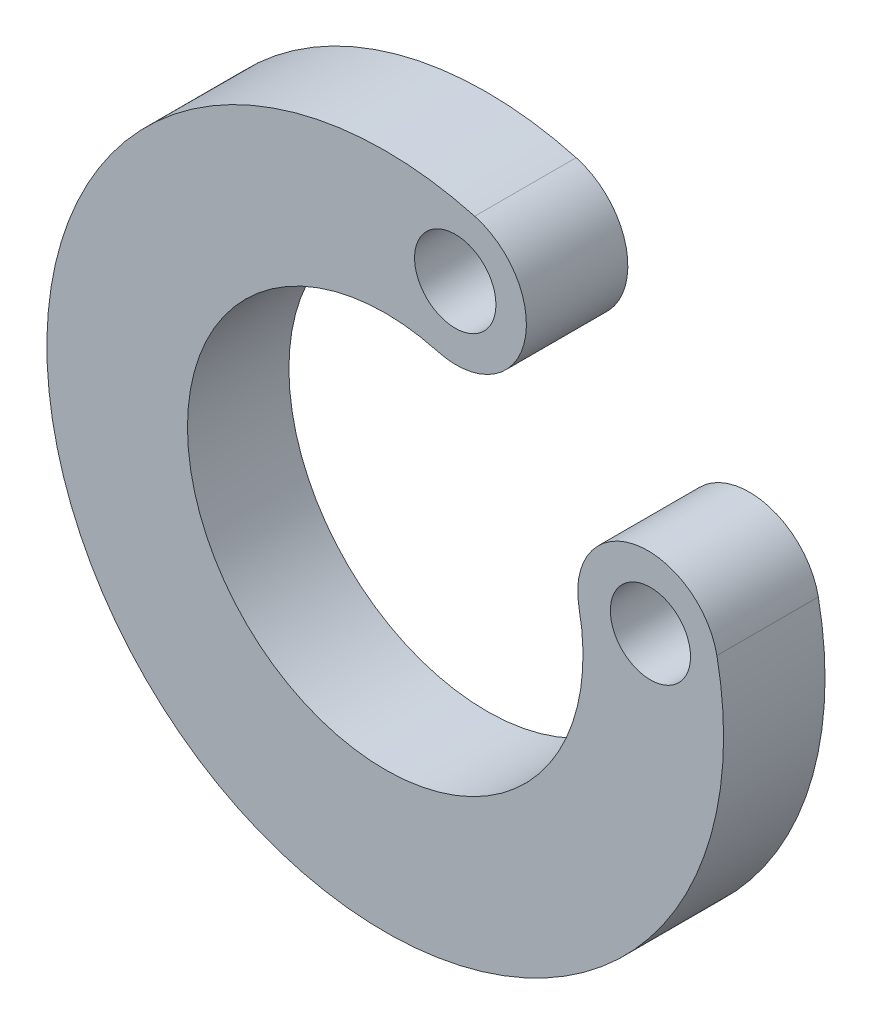
SolidWorks part; units mm, degrees
ref_plane "Front Plane" through (0, 0, 0) normal (0, 0, 1) x (1, 0, 0)
ref_plane "Top Plane" through (0, 0, 0) normal (0, 1, 0) x (1, 0, 0)
ref_plane "Right Plane" through (0, 0, 0) normal (1, 0, 0) x (0, 0, -1)
sketch "Sketch1" plane through (0, 0, 0) normal (0, 0, 1) x (1, 0, 0)
  arc A0 (-35.8212, 29.4604) -> (-16.9063, 9.2064) centre (-42.8084, 3.976) ccw construction
  arc A1 (-33.989, 36.1428) -> (-10.1143, 10.5779) centre (-42.8084, 3.976) ccw
  arc A2 (-37.6533, 22.778) -> (-23.6982, 7.8349) centre (-42.8084, 3.976) ccw
  arc A3 (-37.6533, 22.778) -> (-33.989, 36.1428) centre (-35.8212, 29.4604) ccw
  arc A4 (-10.1143, 10.5779) -> (-23.6982, 7.8349) centre (-16.9063, 9.2064) ccw
  point P3 (-62.1212, -14.06)
extrude "Boss-Extrude1" add sketch "Sketch1" along normal blind 10
sketch "Sketch2" plane through (0, 0, 10) normal (0, 0, 1) x (1, 0, 0)
  circle A0 centre (-35.9072, 29.6322) radius 4.0105
  circle A1 centre (-16.665, 9.1722) radius 3.9509
extrude "Cut-Extrude2" cut sketch "Sketch2" against normal blind 10 contours A1 | A0
